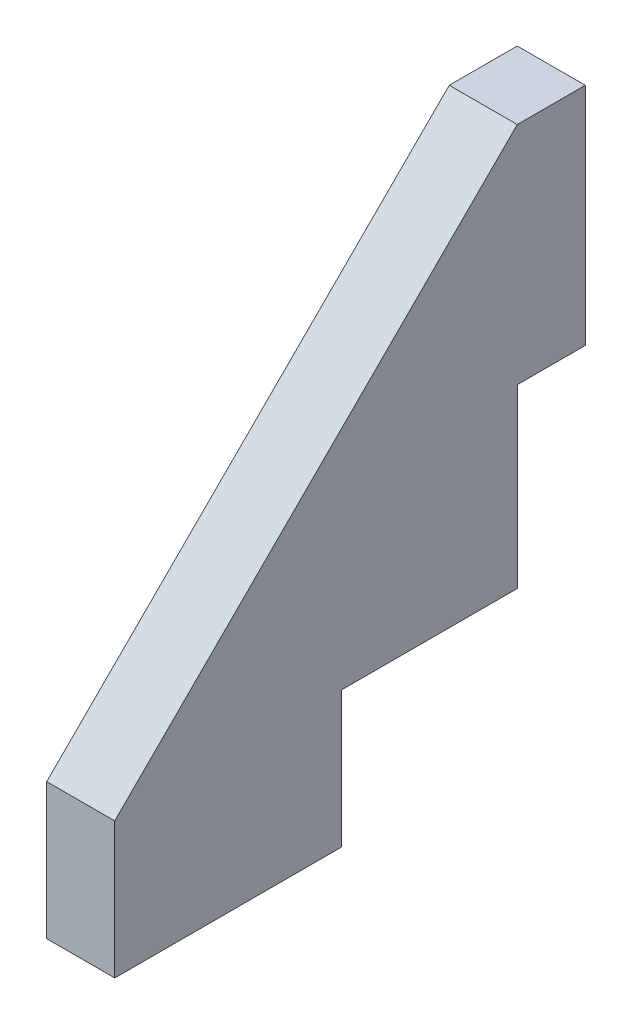
SolidWorks part; units mm, degrees
ref_plane "Front Plane" through (0, 0, 0) normal (0, 0, 1) x (1, 0, 0)
ref_plane "Top Plane" through (0, 0, 0) normal (0, 1, 0) x (1, 0, 0)
ref_plane "Right Plane" through (0, 0, 0) normal (1, 0, 0) x (0, 0, -1)
sketch "Sketch1" plane through (0, 0, 0) normal (1, 0, 0) x (0, 0, -1)
  line L0 (-3, -4.9677) -> (-3, -17.7177)
  line L1 (0, 0) -> (-3, 0)
  line L2 (0, 0) -> (0, -9.9354)
  line L3 (0, -9.9354) -> (-3, -9.9354)
  line L4 (-3, 0) -> (-3, -9.9354)
  line L5 (-3, -17.7177) -> (-15.75, -17.7177)
  line L6 (-20.75, -17.7177) -> (-3, 0)
  line L39 (-20.75, -17.7177) -> (-10.75, -17.7177)
  line L40 (-20.75, -17.7177) -> (-20.75, -23.7177)
  line L41 (-20.75, -23.7177) -> (-10.75, -23.7177)
  line L42 (-10.75, -17.7177) -> (-10.75, -23.7177)
  dimension "D1" = 12.75
  dimension "D2" = 12.75
  dimension "D3" = 25.0794
extrude "Boss-Extrude1" add sketch "Sketch1" along normal blind 3
